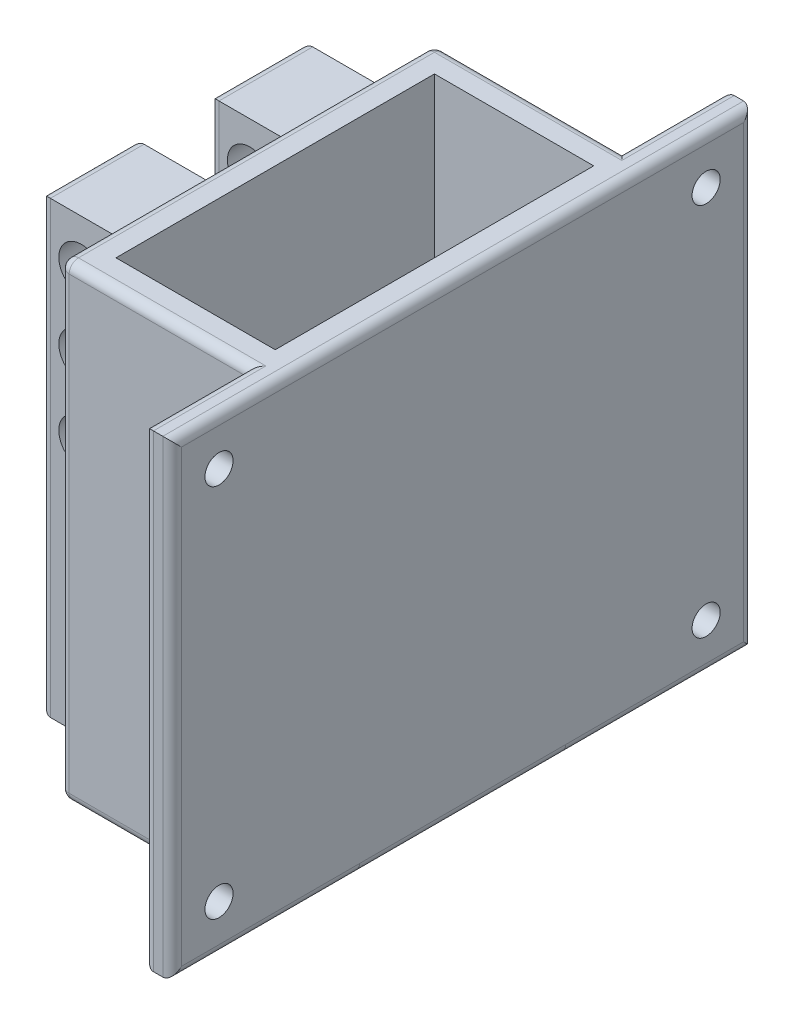
SolidWorks part; units mm, degrees
ref_plane "Alzado" through (0, 0, 0) normal (0, 0, 1) x (1, 0, 0)
ref_plane "Planta" through (0, 0, 0) normal (0, 1, 0) x (1, 0, 0)
ref_plane "Vista lateral" through (0, 0, 0) normal (1, 0, 0) x (0, 0, -1)
sketch "Croquis2" plane through (0, 0, 0) normal (0, 1, 0) x (1, 0, 0)
  line L1 (0, 0) -> (-23, 0)
  line L2 (0, 0) -> (0, 40)
  line L3 (0, 40) -> (-23, 40)
  line L4 (-23, 0) -> (-23, 40)
  dimension "D1" = 40
  dimension "D2" = 23
extrude "Saliente-Extruir1" add sketch "Croquis2" along normal blind 50
sketch "Croquis3" plane through (0, 50, 0) normal (0, 1, 0) x (1, 0, 0)
  line L0 (0, 40) -> (-23, 40) construction
  line L1 (-20, 37) -> (-3, 37)
  line L2 (-20, 37) -> (-20, 3)
  line L3 (-20, 3) -> (-3, 3)
  line L4 (-3, 37) -> (-3, 3)
  line L5 (-23, 40) -> (-23, 0) construction
  line L6 (-23, 0) -> (0, 0) construction
  line L7 (0, 0) -> (0, 40) construction
  dimension "D1" = 3
  dimension "D2" = 3
  dimension "D3" = 3
  dimension "D4" = 3
extrude "Cortar-Extruir1" cut sketch "Croquis3" against normal blind 45
fillet "Redondeo1" radius 1 8 edges at (-23, 25, -40) (0, 25, -40) (0, 25, 0) (-23, 25, 0) (-23, 0, -20) (-11.5, 0, -40) (-11.5, 0, 0) (0, 0, -20)
sketch "Croquis5" plane through (0, 0, 0) normal (1, 0, 0) x (0, 0, -1)
  line L1 (9, 50) -> (-11, 50)
  line L2 (9, 50) -> (9, 0)
  line L3 (9, 0) -> (-11, 0)
  line L4 (-11, 50) -> (-11, 0)
  line L6 (31, 50) -> (51, 50)
  line L7 (31, 50) -> (31, 0)
  line L8 (31, 0) -> (51, 0)
  line L9 (51, 50) -> (51, 0)
  line L10 (39, 1) -> (39, 50) construction
  line L12 (1, 50) -> (1, 1) construction
  line L13 (1, 50) -> (39, 50) construction
  circle A0 centre (-6, 45) radius 1.5
  circle A1 centre (-6, 5) radius 1.5
  circle A2 centre (46, 5) radius 1.5
  circle A3 centre (46, 45) radius 1.5
  dimension "D5" = 3
  dimension "D6" = 3
  dimension "D7" = 3
  dimension "D8" = 3
  dimension "D9" = 5
  dimension "D10" = 5
  dimension "D11" = 5
  dimension "D12" = 5
  dimension "D13" = 5
  dimension "D14" = 5
  dimension "D15" = 5
  dimension "D16" = 5
  dimension "D1" = 50
  dimension "D2" = 50
  dimension "D3" = 20
  dimension "D4" = 20
  dimension "D17" = 30
  dimension "D18" = 30
  dimension "D19" = 50
  dimension "D20" = 50
extrude "Saliente-Extruir3" add sketch "Croquis5" against normal blind 3
fillet "Redondeo2" radius 1 16 edges at (-12.5, 50, 0) (-22.7071, 50, -0.2929) (-23, 50, -20) (-22.7071, 50, -39.7071) (-12.5, 50, -40) (-3, 0, -45) (-3, 25, -51) (-3, 50, -45.5) (0, 25, -51) (0, 0, -41) (0, 0, 1) (0, 25, 11) (-3, 25, 11) (0, 50, -20) (-3, 50, 5.5) (-3, 0, 5)
sketch "Croquis8" plane through (-23, 0, 0) normal (-1, 0, 0) x (0, 0, 1)
  line L1 (-34, 49) -> (-24, 49)
  line L2 (-34, 49) -> (-34, 1)
  line L3 (-34, 1) -> (-24, 1)
  line L4 (-24, 49) -> (-24, 1)
  line L5 (-40, 1) -> (-40, 49) construction
  line L6 (-6, 49) -> (-16, 49)
  line L7 (-6, 49) -> (-6, 1)
  line L8 (-6, 1) -> (-16, 1)
  line L9 (-16, 49) -> (-16, 1)
  line L10 (0, 1) -> (0, 49) construction
  dimension "D1" = 10
  dimension "D2" = 10
  dimension "D3" = 6
  dimension "D4" = 6
extrude "Saliente-Extruir4" add sketch "Croquis8" along normal blind 8
sketch "Croquis9" plane through (0, 0, -6) normal (0, 0, 1) x (1, 0, 0)
  line L1 (-31, 49) -> (-23, 49) construction
  line L3 (-23, 1) -> (-23, 49) construction
  circle A0 centre (-26.7, 28) radius 2.4
  circle A1 centre (-26.7, 36) radius 2.4
  circle A2 centre (-26.7, 44) radius 2.4
  dimension "D1" = 4.8
  dimension "D2" = 4.8
  dimension "D3" = 4.8
  dimension "D4" = 8
  dimension "D5" = 8
  dimension "D6" = 3.7
  dimension "D7" = 5
  dimension "D8" = 3.7
  dimension "D9" = 3.7
extrude "Cortar-Extruir2" cut sketch "Croquis9" against normal through all
fillet "Redondeo3" radius 1 8 edges at (-31, 49, -11) (-31, 49, -29) (-31, 25, -24) (-31, 1, -11) (-31, 25, -16) (-31, 25, -6) (-31, 1, -29) (-31, 25, -34)
